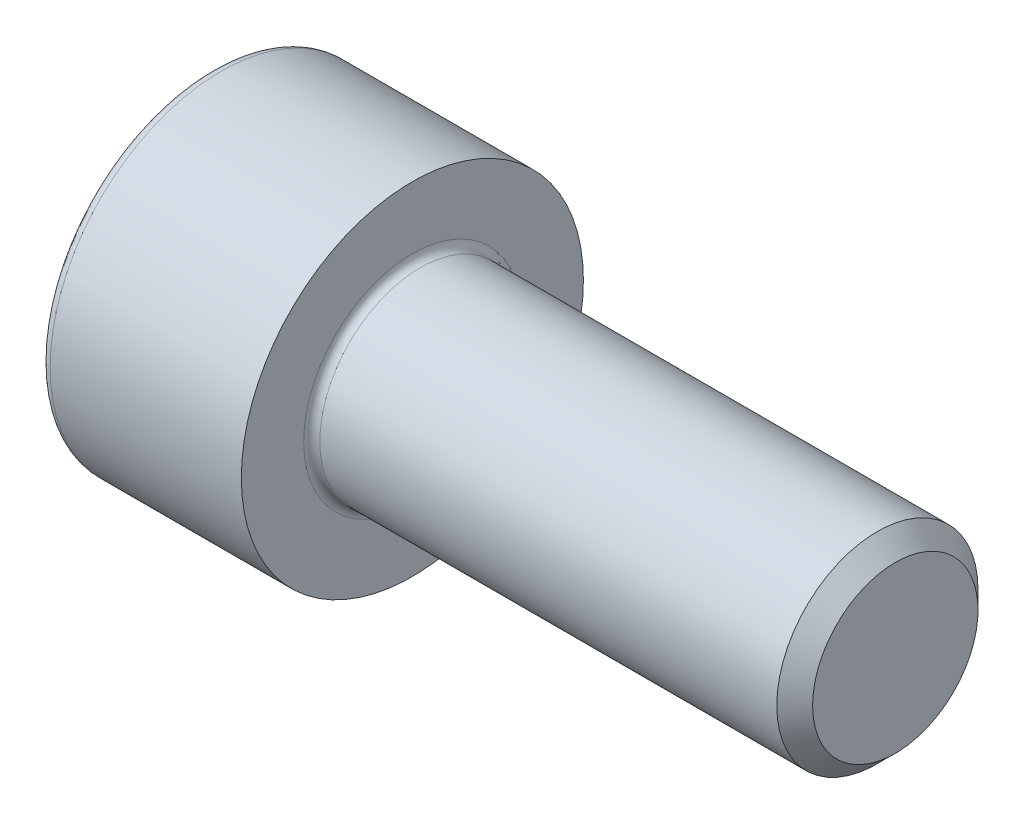
SolidWorks part; units mm, degrees
ref_plane "Front Plane" through (0, 0, 0) normal (0, 0, 1) x (1, 0, 0)
ref_plane "Top Plane" through (0, 0, 0) normal (0, 1, 0) x (1, 0, 0)
ref_plane "Right Plane" through (0, 0, 0) normal (1, 0, 0) x (0, 0, -1)
sketch "BodySke" plane through (0, 0, 0) normal (0, 0, 1) x (1, 0, 0)
  line L0 (0, 0) -> (5.8492, 0) construction
  line L1 (0, 0) -> (0, 4.25)
  line L2 (0, 4.25) -> (5, 4.25)
  line L3 (5, 4.25) -> (5, 2.5)
  line L4 (5, 2.5) -> (16.555, 2.5)
  line L5 (16.555, 2.5) -> (17, 2.055)
  line L6 (17, 2.055) -> (17, 0)
  line L7 (17, 0) -> (0, 0)
  line L8 (5, 0) -> (5, 0.601) construction
  line L9 (5.8, 1.5877) -> (5.8, 0.9267) construction
  dimension "Diameter" = 5
  dimension "Thread_minor" = 4.11
  dimension "Body_chamfer_angle" = 45
  dimension "Length" = 12
  dimension "Head_diameter" = 8.5
  dimension "Head_length" = 5
  dimension "Thread_length" = 12
  dimension "Advance" = 0.8
revolve "BaseBody" add sketch "BodySke" angle 360 about L0
cosmetic thread "ThreadCosmetic" parameters "Thread_length"=12, "Thread_minor"=4.11
fillet "Fillet1" radius 0.2 1 edges at (5, 0, 2.5)
fillet "Fillet2" radius 0.25 1 edges at (0, 0, 4.25)
sketch "HexSke" plane through (0, 0, 0) normal (1, 0, 0) x (0, 0, -1)
  line L1 (0, 2.3094) -> (-2, 1.1547)
  line L2 (-2, 1.1547) -> (-2, -1.1547)
  line L3 (-2, -1.1547) -> (0, -2.3094)
  line L4 (0, -2.3094) -> (2, -1.1547)
  line L5 (2, -1.1547) -> (2, 1.1547)
  line L6 (2, 1.1547) -> (0, 2.3094)
  circle A0 centre (0, 0) radius 2 construction
  dimension "Hex_size" = 4
extrude "Hex" cut sketch "HexSke" along normal blind 2.5
sketch "Hex-PreBroachSke" plane through (0, 0, 0) normal (0, 0, 1) x (1, 0, 0)
  line L0 (0, 0) -> (4.7325, 0) construction
  line L1 (0, 4) -> (0, -4) construction
  line L2 (0, 0) -> (0, 2)
  line L3 (0, 2) -> (2.5, 2)
  line L4 (2.5, 2) -> (3.6547, 0)
  line L5 (3.6547, 0) -> (0, 0)
  dimension "D1" = 4
  dimension "Hex_depth" = 2.5
  dimension "Angle" = 60
revolve "Hex-PreBroach" cut sketch "Hex-PreBroachSke" angle 360 about L0
sketch "ThdSchSke" plane through (0, 0, 0) normal (0, 0, 1) x (1, 0, 0)
  line L0 (0, 0) -> (4.4125, 0) construction
  line L1 (0, 4) -> (0, -4) construction
  line L2 (15.755, 3.0138) -> (15.755, 2.5)
  line L3 (15.755, 3.0138) -> (16.2688, 3.0138)
  line L4 (16.2688, 3.0138) -> (16.2688, 2.5)
  line L5 (16.2688, 2.5) -> (16.0119, 2.055)
  line L6 (16.0119, 2.055) -> (15.755, 2.5)
  dimension "D1" = 0.8
revolve "ThreadSchematic" [suppressed] cut sketch "ThdSchSke" angle 360 about L0
pattern_linear "ThdSchPat" [suppressed]
equation "\"Thread_length@ThreadCosmetic\" = \"Thread_length@BodySke\""
equation "\"Thread_minor@ThreadCosmetic\" = \"Thread_minor@BodySke\""
equation "\"Hex_depth@Hex-PreBroachSke\" = \"Hex_length@Hex\""
equation "\"D1@Hex-PreBroachSke\" = \"Hex_size@HexSke\""
equation "\"D1@ThdSchSke\" = \"Advance@BodySke\""
equation "\"Advance@ThdSchPat\" = \"Advance@BodySke\""
equation "\"Tooth_Num@ThdSchPat\" =  int( \"Thread_length@BodySke\" / \"Advance@BodySke\" )  - 1"
